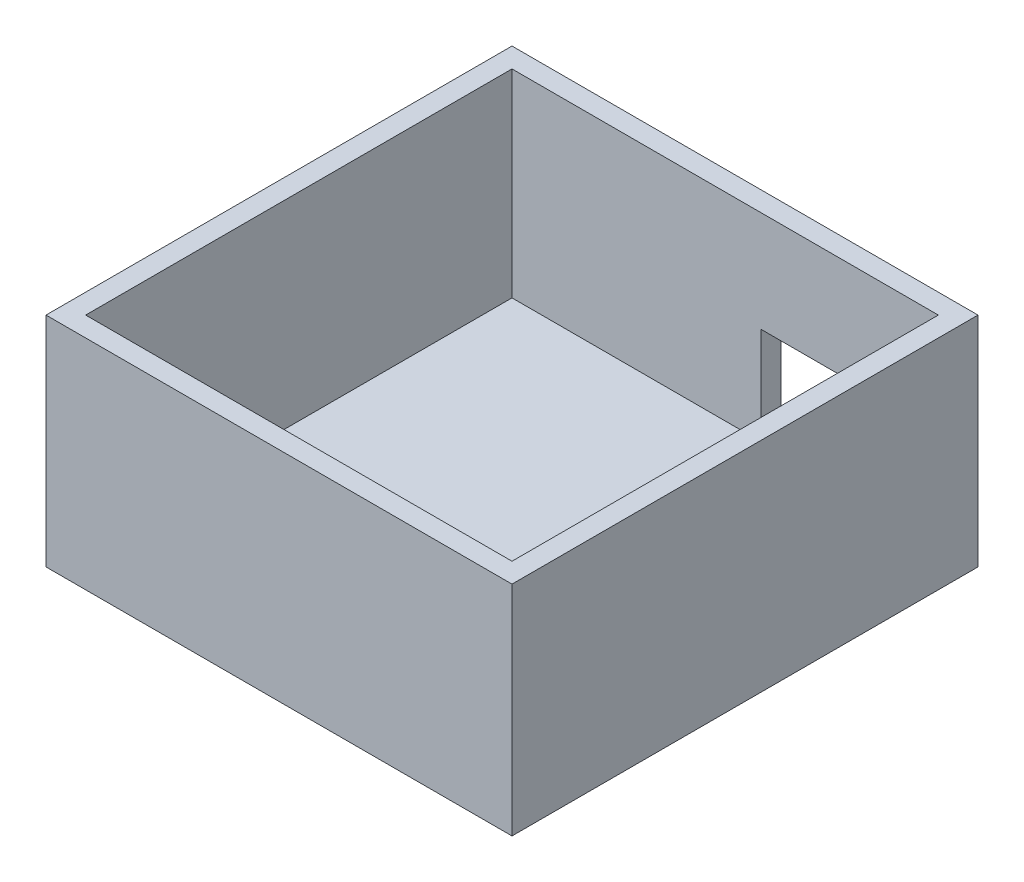
SolidWorks part; units mm, degrees
material "Saf Altın"
ref_plane "Ön Düzlem" through (0, 0, 0) normal (0, 0, 1) x (1, 0, 0)
ref_plane "Üst Düzlem" through (0, 0, 0) normal (0, 1, 0) x (1, 0, 0)
ref_plane "Sağ Düzlem" through (0, 0, 0) normal (1, 0, 0) x (0, 0, -1)
sketch "Çizim2" plane through (0, 0, 0) normal (0, 1, 0) x (1, 0, 0)
  line L0 (-117.5, -112.5) -> (-117.5, -122.5)
  line L1 (-107.5, 102.5) -> (107.5, 102.5)
  line L2 (-107.5, 102.5) -> (-107.5, -112.5)
  line L3 (-107.5, -112.5) -> (107.5, -112.5)
  line L4 (107.5, 102.5) -> (107.5, -112.5)
  line L5 (-107.5, 102.5) -> (107.5, 102.5)
  line L7 (-107.5, 112.5) -> (107.5, 112.5)
  line L10 (-107.5, -112.5) -> (-107.5, 102.5)
  line L11 (-107.5, 112.5) -> (-117.5, 112.5)
  line L12 (-117.5, -112.5) -> (-117.5, 112.5)
  line L13 (-107.5, -112.5) -> (107.5, -112.5)
  line L15 (-107.5, -122.5) -> (107.5, -122.5)
  line L18 (107.5, -112.5) -> (107.5, 102.5)
  line L20 (117.5, -112.5) -> (117.5, 102.5)
  line L21 (-117.5, -122.5) -> (-107.5, -122.5)
  line L22 (107.5, -122.5) -> (117.5, -122.5)
  line L23 (117.5, -122.5) -> (117.5, -112.5)
  line L24 (107.5, 112.5) -> (117.5, 112.5)
  line L25 (117.5, 112.5) -> (117.5, 102.5)
  point P12 (-117.5, 0)
  point P14 (0, 102.5)
  dimension "D1" = 215
  dimension "D2" = 215
  dimension "D3" = 10
  dimension "D4" = 10
  dimension "D5" = 10
  dimension "D6" = 10
extrude "Yükseklik-Ekstrüzyon1" add sketch "Çizim2" along normal blind 100 contours L25 L24 L7 L11 L12 L0 L21 L15 L22 L23 L20 L1 L4 L3 L2
sketch "Çizim3" plane through (0, 0, 0) normal (0, -1, 0) x (1, 0, 0)
  line L1 (-117.5, 122.5) -> (117.5, 122.5)
  line L2 (-117.5, 122.5) -> (-117.5, -112.5)
  line L3 (-117.5, -112.5) -> (117.5, -112.5)
  line L4 (117.5, 122.5) -> (117.5, -112.5)
extrude "Yükseklik-Ekstrüzyon2" add sketch "Çizim3" along normal blind 10
sketch "Çizim5" plane through (0, 0, -112.5) normal (0, 0, -1) x (-1, 0, 0)
  line L1 (-92.875, 49.07) -> (-18.1395, 49.07)
  line L2 (-92.875, 49.07) -> (-92.875, 8.6996)
  line L3 (-92.875, 8.6996) -> (-18.1395, 8.6996)
  line L4 (-18.1395, 49.07) -> (-18.1395, 8.6996)
extrude "Kes-Ekstrüzyon1" cut sketch "Çizim5" against normal up to next
